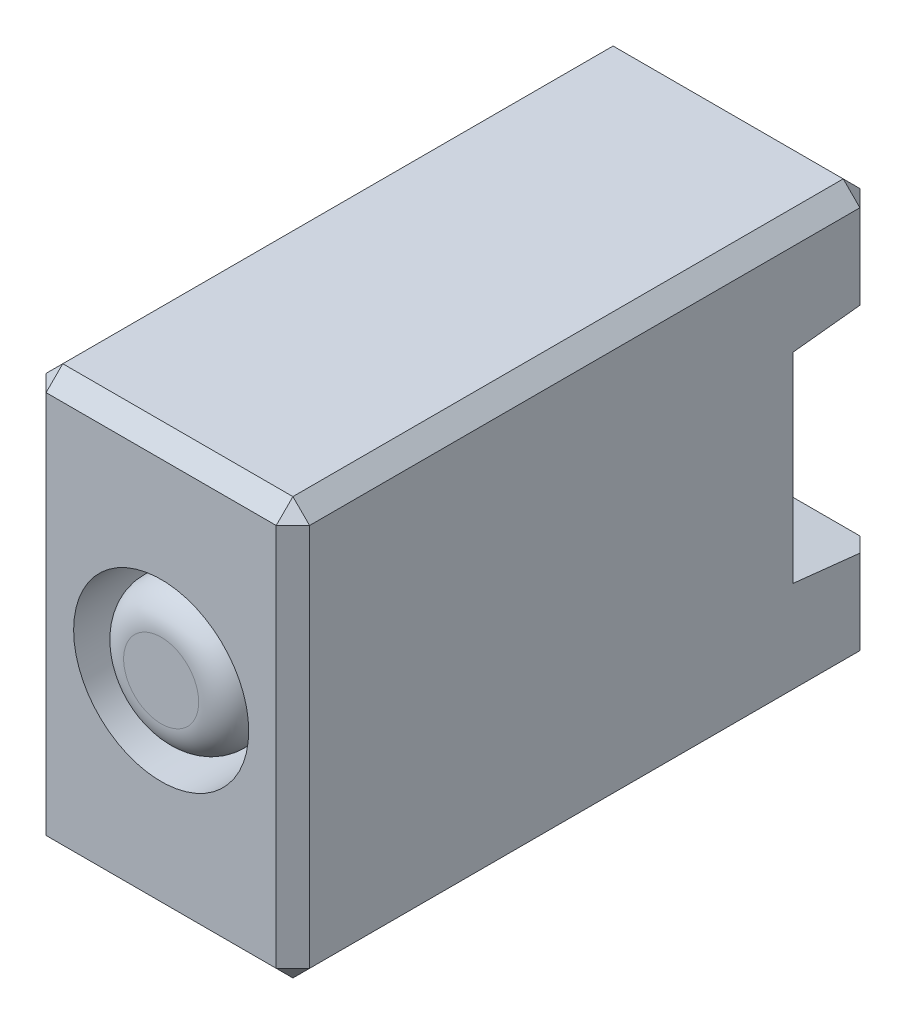
SolidWorks part; units mm, degrees
ref_plane "정면" through (0, 0, 0) normal (0, 0, 1) x (1, 0, 0)
ref_plane "윗면" through (0, 0, 0) normal (0, 1, 0) x (1, 0, 0)
ref_plane "우측면" through (0, 0, 0) normal (1, 0, 0) x (0, 0, -1)
sketch "스케치3" plane through (0, 0, 0) normal (0, 0, 1) x (1, 0, 0)
  line L1 (-7.9, 12.5) -> (7.9, 12.5)
  line L2 (-7.9, 12.5) -> (-7.9, -12.5)
  line L3 (-7.9, -12.5) -> (7.9, -12.5)
  line L4 (7.9, 12.5) -> (7.9, -12.5)
  line L5 (-7.9, 12.5) -> (7.9, -12.5) construction
  line L6 (-7.9, -12.5) -> (7.9, 12.5) construction
  point P0 (0, 0)
  dimension "D1" = 15.8
  dimension "D2" = 25
extrude "보스-돌출2" add sketch "스케치3" along normal blind 35
sketch "스케치4" plane through (0, 0, 35) normal (0, 0, 1) x (1, 0, 0)
  circle A0 centre (0, 0) radius 5.25
  circle A1 centre (0, 0) radius 4.25
  dimension "D1" = 10.5
  dimension "D2" = 8.5
extrude "컷-돌출1" cut sketch "스케치4" against normal blind 10
sketch "스케치5" plane through (0, 0, 0) normal (1, 0, 0) x (0, 0, -1)
  line L0 (2.1091, 6.77) -> (-5, 6.0043)
  line L1 (-5, 6.0043) -> (-5, -6.0043)
  line L2 (2.1091, -6.77) -> (-5, -6.0043)
  line L3 (2.1091, -6.77) -> (2.1091, 6.77)
  line L4 (0, 0) -> (-4.8962, 0) construction
  dimension "D2" = 5
extrude "컷-돌출3" cut sketch "스케치5" against normal through all both and the other way through all contours L0 L1 L2 L3
fillet "필렛1" radius 2 1 edges at (4.25, 0, 35)
chamfer "모따기1" distance 1 angle 45 14 edges at (0, 12.5, 35) (0, -12.5, 35) (0, 12.5, 0) (0, -12.5, 0) (7.9, 12.5, 17.5) (-7.9, 12.5, 17.5) (7.9, -12.5, 17.5) (-7.9, -12.5, 17.5) (7.9, 9.5214, 0) (-7.9, 9.5214, 0) (7.9, -9.5214, 0) (-7.9, -9.5214, 0) (-7.9, 0, 35) (7.9, 0, 35)
